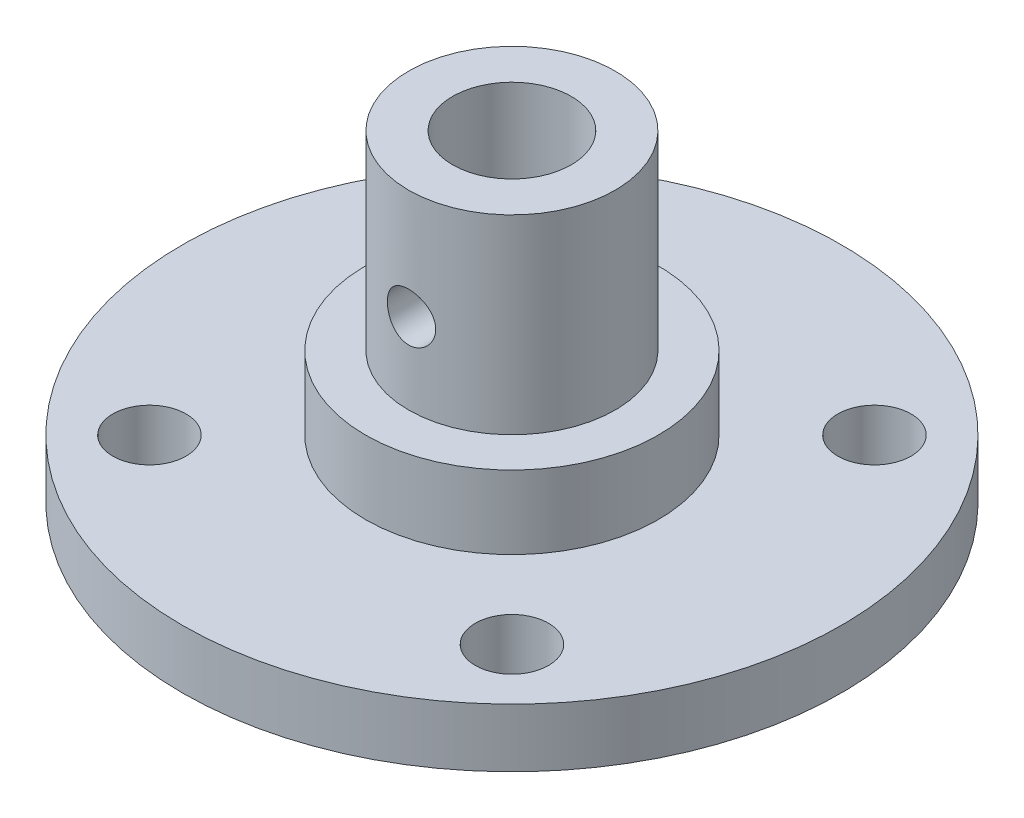
SolidWorks part; units mm, degrees
ref_plane "Front Plane" through (0, 0, 0) normal (0, 0, 1) x (1, 0, 0)
ref_plane "Top Plane" through (0, 0, 0) normal (0, 1, 0) x (1, 0, 0)
ref_plane "Right Plane" through (0, 0, 0) normal (1, 0, 0) x (0, 0, -1)
sketch "Sketch1" plane through (0, 0, 0) normal (0, 1, 0) x (1, 0, 0)
  circle A0 centre (0, 0) radius 22.5
  circle A1 centre (0, 0) radius 17.5 construction
  circle A3 centre (-12.3744, 12.3744) radius 2.5
  circle A5 centre (12.3744, 12.3744) radius 2.5
  circle A7 centre (12.3744, -12.3744) radius 2.5
  circle A9 centre (-12.3744, -12.3744) radius 2.5
  point P15 (0, 0)
  dimension "D1" = 35
  dimension "D2" = 5
  dimension "D3" = 45
extrude "Boss-Extrude1" add sketch "Sketch1" along normal blind 4
sketch "Sketch2" plane through (0, 4, 0) normal (0, 1, 0) x (1, 0, 0)
  circle A0 centre (0, 0) radius 4.05
  circle A1 centre (0, 0) radius 7.05
  dimension "D1" = 3
  dimension "D2" = 8.1
extrude "Boss-Extrude2" add sketch "Sketch2" along normal blind 18
sketch "Sketch3" plane through (0, 0, 0) normal (0, 0, 1) x (1, 0, 0)
  line L0 (4.05, 22) -> (-4.05, 22) construction
  circle A0 centre (0, 14.5) radius 1.65
  dimension "D1" = 7.5
  dimension "D2" = 3.3
extrude "Cut-Extrude1" cut sketch "Sketch3" against normal mid plane 18
sketch "Sketch4" plane through (0, 4, 0) normal (0, 1, 0) x (1, 0, 0)
  circle A0 centre (0, 0) radius 10
  circle A2 centre (0, 0) radius 7
extrude "Boss-Extrude3" add sketch "Sketch4" along normal blind 5
